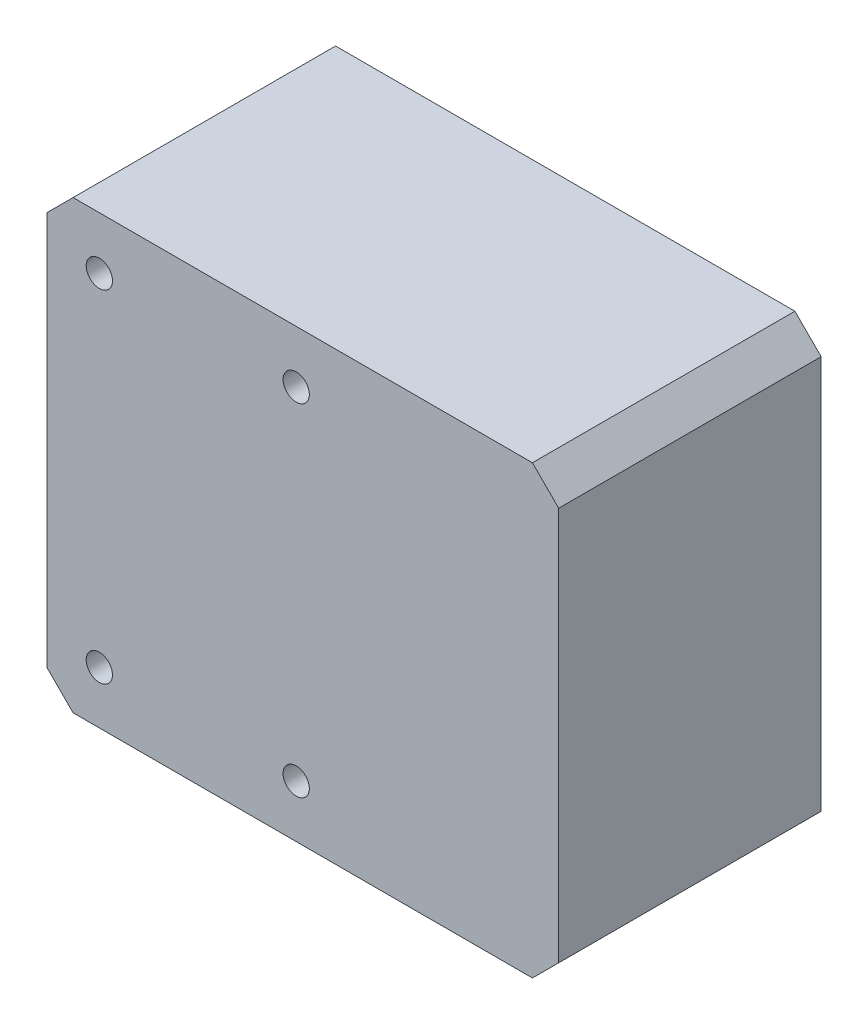
SolidWorks part; units mm, degrees
material "可锻铸铁"
ref_plane "前视基准面" through (0, 0, 0) normal (0, 0, 1) x (1, 0, 0)
ref_plane "上视基准面" through (0, 0, 0) normal (0, 1, 0) x (1, 0, 0)
ref_plane "右视基准面" through (0, 0, 0) normal (1, 0, 0) x (0, 0, -1)
sketch "草图1" plane through (0, 0, 0) normal (0, 0, 1) x (1, 0, 0)
  line L0 (-57.5, 0) -> (0, 0) construction
  line L1 (-37.5, -65) -> (37.5, -65) construction
  line L2 (-37.5, -65) -> (-37.5, 65) construction
  line L3 (-37.5, 65) -> (37.5, 65) construction
  line L4 (37.5, -65) -> (37.5, 65) construction
  line L5 (-37.5, -65) -> (37.5, 65) construction
  line L6 (-37.5, 65) -> (37.5, -65) construction
  line L7 (-57.5, -85) -> (137.5, -85)
  line L8 (-57.5, -85) -> (-57.5, 85)
  line L9 (-57.5, 85) -> (137.5, 85)
  line L10 (137.5, -85) -> (137.5, 85)
  circle A0 centre (-37.5, 65) radius 5
  circle A1 centre (37.5, 65) radius 5
  circle A2 centre (-37.5, -65) radius 5
  circle A3 centre (37.5, -65) radius 5
  point P0 (0, 0)
  point P10 (0, 0)
  dimension "D3" = 10
  dimension "D1" = 75
  dimension "D2" = 130
  dimension "D4" = 20
  dimension "D5" = 20
  dimension "D6" = 100
extrude "凸台-拉伸1" add sketch "草图1" along normal blind 100
chamfer "倒角1" distance 10 angle 45 4 edges at (-57.5, 85, 50) (-57.5, -85, 50) (137.5, -85, 50) (137.5, 85, 50)
